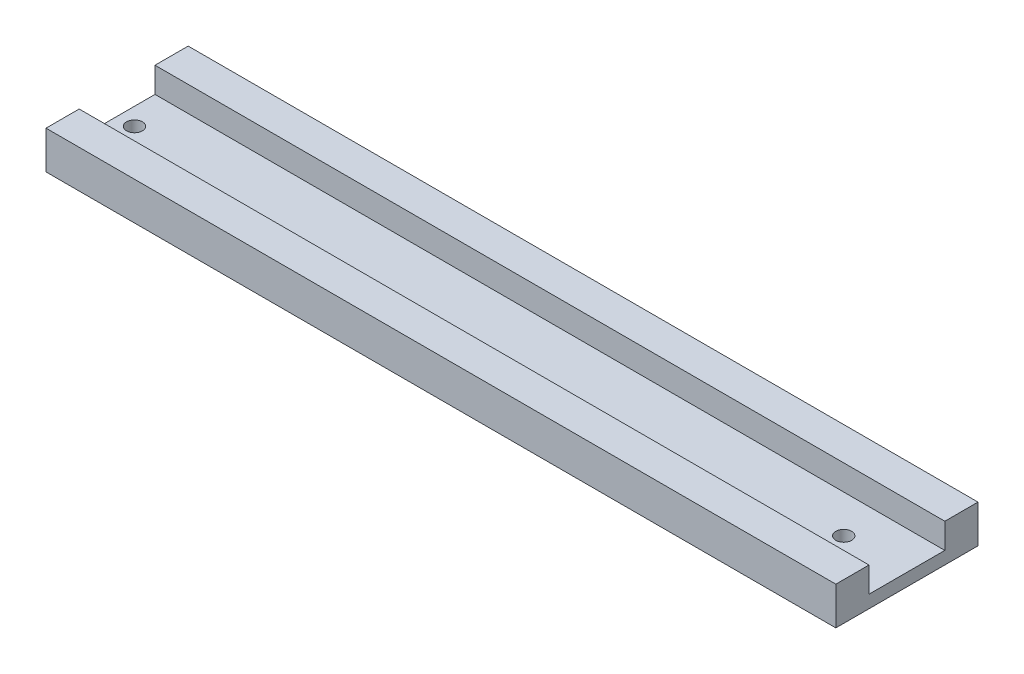
SolidWorks part; units mm, degrees
material "普通碳钢"
ref_plane "前视基准面" through (0, 0, 0) normal (0, 0, 1) x (1, 0, 0)
ref_plane "上视基准面" through (0, 0, 0) normal (0, 1, 0) x (1, 0, 0)
ref_plane "右视基准面" through (0, 0, 0) normal (1, 0, 0) x (0, 0, -1)
sketch "草图2" plane through (0, 0, 0) normal (1, 0, 0) x (0, 0, -1)
  line L1 (-22.5, -6) -> (22.5, -6)
  line L2 (-22.5, -6) -> (-22.5, 6)
  line L3 (-22.5, 6) -> (22.5, 6)
  line L4 (22.5, -6) -> (22.5, 6)
  line L5 (-22.5, -6) -> (22.5, 6) construction
  line L6 (-22.5, 6) -> (22.5, -6) construction
  line L7 (-12, -2) -> (12, -2)
  line L8 (-12, -2) -> (-12, 6)
  line L9 (-12, 6) -> (12, 6)
  line L10 (12, -2) -> (12, 6)
  line L11 (-12, -2) -> (12, 6) construction
  line L12 (-12, 6) -> (12, -2) construction
  point P0 (0, 0)
  point P6 (0, 2)
  dimension "D1" = 45
  dimension "D2" = 12
  dimension "D3" = 24
  dimension "D4" = 8
extrude "凸台-拉伸1" add sketch "草图2" along normal blind 250 contours L10 L7 L8 L3 L2 L1 L4
sketch "草图3" plane through (0, 0, 0) normal (1, 0, 0) x (0, 0, -1)
  line L0 (-12, -2) -> (12, -2) construction
  line L1 (-12, -2) -> (12, -2)
  line L2 (-12, -2) -> (-12, 6)
  line L3 (-12, 6) -> (12, 6)
  line L4 (12, -2) -> (12, 6)
  line L5 (-12, -2) -> (12, 6) construction
  line L6 (-12, 6) -> (12, -2) construction
  point P0 (0, 2)
  dimension "D1" = 24
  dimension "D2" = 8
sketch "草图4" plane through (0, 0, 0) normal (0, 1, 0) x (1, 0, 0)
  line L0 (250, -12) -> (250, 12) construction
  circle A2 centre (230, 0) radius 2.5
  circle A3 centre (5.5, 0) radius 2.5
  point P0 (230, 0)
  dimension "D1" = 20
  dimension "D2" = 5
  dimension "D5" = 5
  dimension "D3" = 230
  dimension "D4" = 5.5
extrude "切除-拉伸1" cut sketch "草图4" against normal through all
